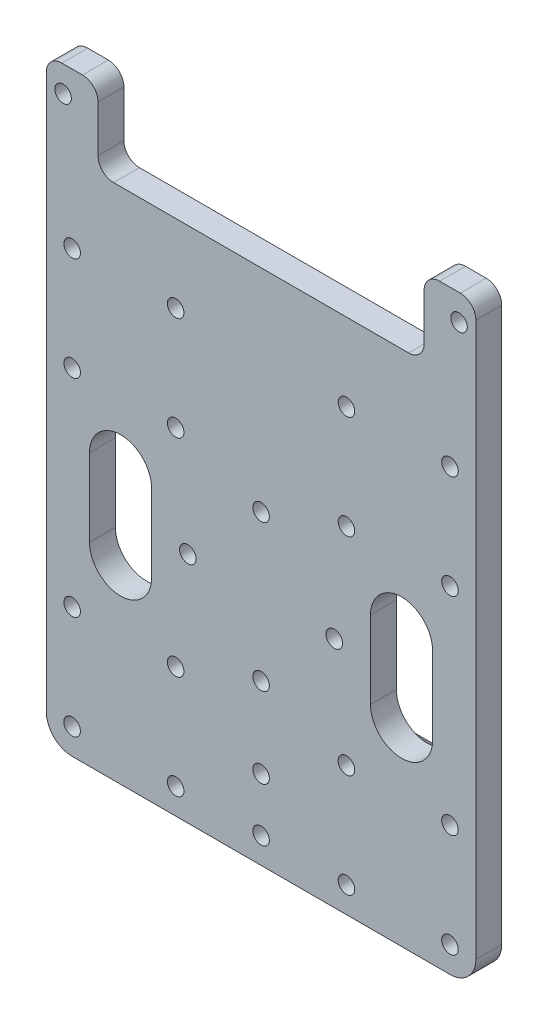
SolidWorks part; units mm, degrees
material "ぶな"
ref_plane "正面" through (0, 0, 0) normal (0, 0, 1) x (1, 0, 0)
ref_plane "平面" through (0, 0, 0) normal (0, 1, 0) x (1, 0, 0)
ref_plane "右側面" through (0, 0, 0) normal (1, 0, 0) x (0, 0, -1)
sketch "ｽｹｯﾁ1" plane through (0, 0, 0) normal (0, 0, 1) x (1, 0, 0)
  line L0 (0, 14.1421) -> (0, 0) construction
  line L1 (0, 0) -> (14.1421, 0) construction
  line L2 (36.5, -20) -> (36.5, -40) construction
  line L3 (16.5, 20) -> (36.5, 20) construction
  line L4 (16.5, 20) -> (16.5, 40) construction
  line L5 (16.5, 40) -> (36.5, 40) construction
  line L6 (36.5, 20) -> (36.5, 40) construction
  line L7 (16.5, -40) -> (36.5, -40) construction
  line L8 (16.5, -20) -> (16.5, -40) construction
  line L9 (16.5, -20) -> (36.5, -20) construction
  line L10 (-16.5, -20) -> (-36.5, -20) construction
  line L11 (-16.5, -20) -> (-16.5, -40) construction
  line L12 (-16.5, -40) -> (-36.5, -40) construction
  line L13 (-36.5, 20) -> (-36.5, 40) construction
  line L14 (-16.5, 40) -> (-36.5, 40) construction
  line L15 (-16.5, 20) -> (-16.5, 40) construction
  line L16 (-16.5, 20) -> (-36.5, 20) construction
  line L17 (-36.5, -20) -> (-36.5, -40) construction
  line L19 (36.5, -45) -> (-36.5, -45)
  line L20 (41.5, -40) -> (41.5, 40)
  line L21 (36.5, 45) -> (-36.5, 45)
  line L22 (-41.5, -40) -> (-41.5, 40)
  line L23 (41.5, -45) -> (-41.5, 45) construction
  line L24 (41.5, 45) -> (-41.5, -45) construction
  circle A0 centre (16.5, 40) radius 1.6
  circle A1 centre (16.5, 20) radius 1.6
  circle A2 centre (36.5, 20) radius 1.6
  circle A3 centre (36.5, 40) radius 1.6
  circle A4 centre (36.5, -40) radius 1.6
  circle A5 centre (36.5, -20) radius 1.6
  circle A6 centre (16.5, -20) radius 1.6
  circle A7 centre (16.5, -40) radius 1.6
  circle A8 centre (-16.5, -40) radius 1.6
  circle A9 centre (-16.5, -20) radius 1.6
  circle A10 centre (-36.5, -20) radius 1.6
  circle A11 centre (-36.5, -40) radius 1.6
  circle A12 centre (-36.5, 40) radius 1.6
  circle A13 centre (-36.5, 20) radius 1.6
  circle A14 centre (-16.5, 20) radius 1.6
  circle A15 centre (-16.5, 40) radius 1.6
  arc A16 (41.5, 40) -> (36.5, 45) centre (36.5, 40) ccw
  arc A17 (36.5, -45) -> (41.5, -40) centre (36.5, -40) ccw
  arc A18 (-36.5, -45) -> (-41.5, -40) centre (-36.5, -40) cw
  arc A19 (-36.5, 45) -> (-41.5, 40) centre (-36.5, 40) ccw
  circle A20 centre (14.1421, 0) radius 1.6
  circle A21 centre (0, -14.1421) radius 1.6
  circle A22 centre (-14.1421, 0) radius 1.6
  circle A23 centre (0, 14.1421) radius 1.6
  point P53 (0, -17.8696)
  point P54 (0, 0)
  point P55 (0, 15)
  point P62 (0, 0)
  dimension "D1" = 3.2
  dimension "D5" = 5
  dimension "D6" = 4
  dimension "D2" = 20
  dimension "D3" = 33
  dimension "D4" = 40
  dimension "D7" = 20
extrude "ﾎﾞｽ - 押し出し1" add sketch "ｽｹｯﾁ1" along normal blind 5
sketch "ｽｹｯﾁ7" plane through (0, 0, 0) normal (0, 0, -1) x (-1, 0, 0)
  line L0 (0, 45) -> (0, 55) construction
  line L3 (-38.25, 65) -> (38.25, 65) construction
  line L5 (-36.5, 45) -> (36.5, 45) construction
  line L6 (-41.5, 40) -> (-41.5, 67)
  line L7 (-38.5, 70) -> (-34.5, 70)
  line L8 (41.5, 67) -> (41.5, 40)
  line L15 (-36.5, 45) -> (36.5, 45)
  line L16 (31.5, 67) -> (31.5, 58)
  line L17 (28.5, 55) -> (-28.5, 55)
  line L18 (-31.5, 67) -> (-31.5, 58)
  line L19 (34.5, 70) -> (38.5, 70)
  circle A1 centre (-38.25, 65) radius 1.6
  circle A3 centre (38.25, 65) radius 1.6
  arc A4 (-36.5, 45) -> (-41.5, 40) centre (-36.5, 40) ccw construction
  arc A5 (41.5, 40) -> (36.5, 45) centre (36.5, 40) ccw construction
  arc A6 (38.5, 70) -> (41.5, 67) centre (38.5, 67) cw
  arc A7 (-41.5, 67) -> (-38.5, 70) centre (-38.5, 67) cw
  arc A12 (41.5, 40) -> (36.5, 45) centre (36.5, 40) ccw
  arc A13 (-36.5, 45) -> (-41.5, 40) centre (-36.5, 40) ccw
  arc A14 (-31.5, 67) -> (-34.5, 70) centre (-34.5, 67) ccw
  arc A15 (31.5, 67) -> (34.5, 70) centre (34.5, 67) cw
  arc A16 (-31.5, 58) -> (-28.5, 55) centre (-28.5, 58) ccw
  arc A17 (31.5, 58) -> (28.5, 55) centre (28.5, 58) cw
  point P0 (-36.5, 65)
  point P3 (0, 65)
  point P23 (-29.2014, 56.8899)
  point P25 (-31.5, 70)
  point P32 (31.5, 70)
  point P35 (-31.5, 55)
  point P38 (31.5, 55)
  dimension "D3" = 3.2
  dimension "D5" = 3
  dimension "D8" = 10
  dimension "D9" = 3
  dimension "D10" = 3
  dimension "D2" = 76.5
  dimension "D4" = 20
  dimension "D6" = 5
  dimension "D7" = 10
extrude "ﾎﾞｽ - 押し出し3" add sketch "ｽｹｯﾁ7" against normal up to surface (5 mm away) up to face at (-12.5421, 0, 5)
sketch "ｽｹｯﾁ8" plane through (0, 0, 0) normal (0, 0, -1) x (-1, 0, 0)
  line L0 (0, 0) -> (-41.5, 0) construction
  line L1 (-41.5, -40) -> (-41.5, 67) construction
  line L2 (-27.1421, -7.5) -> (-27.1421, 7.5) construction
  line L3 (28.5, 55) -> (-28.5, 55) construction
  line L4 (0, 55) -> (0, 0) construction
  line L5 (-33.1421, -7.5) -> (-33.1421, 7.5)
  line L6 (-21.1421, -7.5) -> (-21.1421, 7.5)
  line L7 (27.1421, -7.5) -> (27.1421, 7.5) construction
  line L8 (33.1421, -7.5) -> (33.1421, 7.5)
  line L9 (21.1421, -7.5) -> (21.1421, 7.5)
  arc A0 (-33.1421, -7.5) -> (-21.1421, -7.5) centre (-27.1421, -7.5) ccw
  arc A1 (-21.1421, 7.5) -> (-33.1421, 7.5) centre (-27.1421, 7.5) ccw
  arc A2 (33.1421, -7.5) -> (21.1421, -7.5) centre (27.1421, -7.5) cw
  arc A3 (21.1421, 7.5) -> (33.1421, 7.5) centre (27.1421, 7.5) cw
  circle A4 centre (-14.1421, 0) radius 1.6 construction
  point P10 (-27.1421, 0)
  point P17 (27.1421, 0)
  point P22 (-20.5741, 0)
  dimension "D1" = 6
  dimension "D2" = 15
  dimension "D3" = 7
extrude "ｶｯﾄ - 押し出し1" cut sketch "ｽｹｯﾁ8" against normal through all
sketch "ｽｹｯﾁ9" plane through (0, 0, 0) normal (1, 0, 0) x (0, 0, -1)
  line L0 (0, -25) -> (0, -50)
  line L1 (0, -40) -> (0, 67) construction
  line L2 (0, -50) -> (30, -50)
  line L3 (30, -50) -> (30, -43)
  line L4 (30, -43) -> (7, -25)
  line L5 (7, -25) -> (0, -25)
  line L6 (-5, -45) -> (0, -45) construction
  point P6 (0, 0)
  point P9 (0, -49.9748)
  dimension "D1" = 7
  dimension "D2" = 7
  dimension "D3" = 5
  dimension "D4" = 30
  dimension "D5" = 20
extrude "ﾎﾞｽ - 押し出し4" add sketch "ｽｹｯﾁ9" along normal mid plane 10 separate body
sketch "ｽｹｯﾁ10" plane through (0, 0, 5) normal (0, 0, 1) x (1, 0, 0)
  line L0 (5, -25) -> (5, -50) construction
  line L1 (5, -25) -> (-5, -25) construction
  line L2 (-5, -25) -> (-5, -50) construction
  line L3 (5, -25) -> (5, -50) construction
  line L4 (5, -25) -> (-5, -25) construction
  line L5 (-5, -25) -> (-5, -50) construction
  line L6 (0, -25) -> (0, -45) construction
  line L7 (-36.5, -45) -> (36.5, -45) construction
  circle A0 centre (0, -29.6737) radius 1.6
  circle A1 centre (0, -40) radius 1.6
  dimension "D1" = 3.2
  dimension "D2" = 4.6737
  dimension "D3" = 5
extrude "ｶｯﾄ - 押し出し2" cut sketch "ｽｹｯﾁ10" against normal up to surface (5 mm away) up to face at (27.1421, 0, 0)
sketch "ｽｹｯﾁ11" plane through (0, 0, 0) normal (0, 0, 1) x (1, 0, 0)
  circle A0 centre (0, -29.6737) radius 1.3
  circle A1 centre (0, -40) radius 1.3
  dimension "D1" = 2.6
extrude "ｶｯﾄ - 押し出し3" cut sketch "ｽｹｯﾁ11" against normal through all
